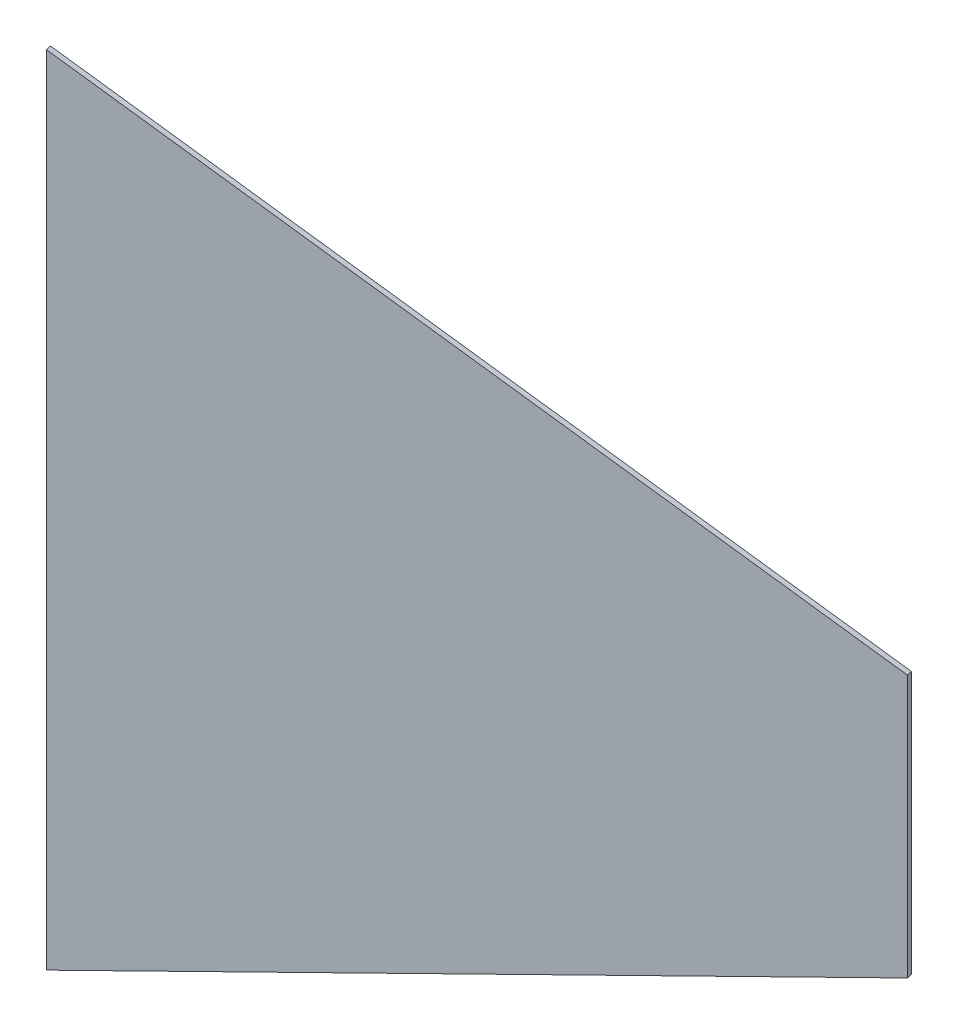
SolidWorks part; units mm, degrees
ref_plane "Front Plane" through (0, 0, 0) normal (0, 0, 1) x (1, 0, 0)
ref_plane "Top Plane" through (0, 0, 0) normal (0, 1, 0) x (1, 0, 0)
ref_plane "Right Plane" through (0, 0, 0) normal (1, 0, 0) x (0, 0, -1)
ref_plane "Plane1" through (161.0176, 0, 726.3033) normal (0.2164, 0, 0.9763) x (0, 1, 0)
sketch "Sketch1" plane through (161.0176, 0, 726.3033) normal (0.2164, 0, 0.9763) x (0, 1, 0)
  line L0 (-236.8034, 530.4553) -> (-24.5604, 0) construction
  line L1 (-24.5604, 0) -> (24.5604, 0) construction
  line L2 (24.5604, 0) -> (236.8034, 530.4553) construction
  line L3 (236.8034, 530.4553) -> (-236.8034, 530.4553)
  line L4 (-65.2121, 101.6) -> (65.2121, 101.6) construction
  line L5 (0, 0) -> (0, 101.6) construction
  line L6 (65.2121, 101.6) -> (77.9121, 101.6) construction
  line L7 (236.8034, 530.4553) -> (77.9121, 101.6)
  line L8 (-236.8034, 530.4553) -> (-77.9121, 101.6)
  line L9 (-77.9121, 101.6) -> (77.9121, 101.6)
  point P7 (0, 0)
  dimension "D2" = 571.3404
  dimension "D3" = 49.1208
  dimension "D4" = 473.6068
  dimension "D5" = 101.6
  dimension "D6" = 12.7
extrude "Boss-Extrude1" add sketch "Sketch1" against normal blind 3.175
